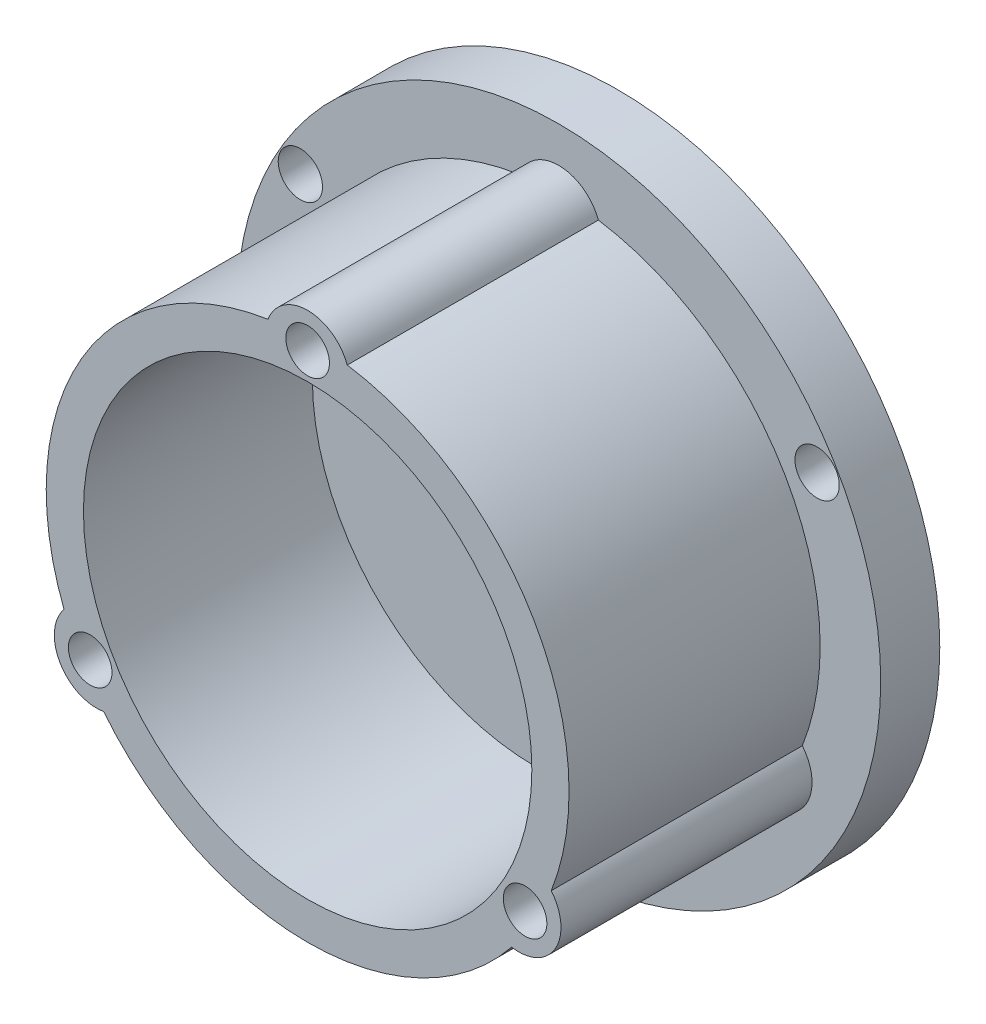
SolidWorks part; units mm, degrees
ref_plane "前视基准面" through (0, 0, 0) normal (0, 0, 1) x (1, 0, 0)
ref_plane "上视基准面" through (0, 0, 0) normal (0, 1, 0) x (1, 0, 0)
ref_plane "右视基准面" through (0, 0, 0) normal (1, 0, 0) x (0, 0, -1)
sketch "草图1" plane through (0, 0, 0) normal (0, 0, 1) x (1, 0, 0)
  circle A0 centre (0, 0) radius 15.75
  circle A1 centre (0, 0) radius 23 construction
  circle A3 centre (0, 0) radius 20
extrude "凸台-拉伸1" add sketch "草图1" along normal blind 5
sketch "草图2" plane through (0, 0, 5) normal (0, 0, 1) x (1, 0, 0)
  circle A0 centre (0, 0) radius 24 construction
  arc A2 (0, -25.8924) -> (22.4235, 12.9462) centre (20.7846, -12) ccw
  arc A3 (-22.4235, 12.9462) -> (0, -25.8924) centre (-20.7846, -12) ccw
  arc A5 (22.4235, 12.9462) -> (-22.4235, 12.9462) centre (0, 24) ccw
  point P12 (0, 0)
extrude "凸台-拉伸2" add sketch "草图2" along normal blind 8
sketch "草图3" plane through (0, 0, 13) normal (0, 0, 1) x (1, 0, 0)
  circle A0 centre (0, 42) radius 18
  circle A1 centre (36.3731, -21) radius 18
  circle A2 centre (-36.3731, -21) radius 18
  point P3 (0, 42)
  point P10 (0, 0)
  dimension "D1" = 3
  dimension "D3" = 42
extrude "凸台-拉伸3" add sketch "草图3" along normal blind 13
sketch "草图8" plane through (0, 0, 5) normal (0, 0, -1) x (-1, 0, 0)
  line L0 (0, 42) -> (36.3731, -21) construction
  line L1 (0, 0) -> (18.1865, 10.5) construction
  line L2 (18.1865, 10.5) -> (86.4245, 49.8972) construction
  line L3 (0, 0) -> (0, -8.0959) construction
  circle A0 centre (0, 0) radius 42 construction
  circle A4 centre (0, 42) radius 22
  circle A5 centre (36.3731, -21) radius 22
  circle A6 centre (-36.3731, -21) radius 22
  arc A7 (21.7226, 45.4827) -> (50.2505, -3.929) centre (100.7138, 58.1471) ccw
  arc A8 (-21.7226, 45.4827) -> (-50.2505, -3.929) centre (-100.7138, 58.1471) cw
  arc A9 (28.5279, -41.5537) -> (-28.5279, -41.5537) centre (0, -116.2943) ccw
  point P12 (0, 0)
  point P14 (0, 0)
  arc M7 (22.4235, 12.9462) -> (-22.4235, 12.9462) centre (0, 24) ccw
  arc M9 (-22.4235, 12.9462) -> (0, -25.8924) centre (-20.7846, -12) ccw
  arc M11 (0, -25.8924) -> (22.4235, 12.9462) centre (20.7846, -12) ccw
  dimension "D1" = 3
extrude "凸台-拉伸6" add sketch "草图8" against normal up to surface (8 mm away) contours A4 M7 | A7 A4 A5 M7 M11 | A5 M11 | A9 A5 A6 M11 M9 | A6 M9 | A4 A8 A6 M9 M7
sketch "草图4" plane through (0, 0, 26) normal (0, 0, 1) x (1, 0, 0)
  circle A0 centre (0, 42) radius 15
  circle A1 centre (36.3731, -21) radius 15
  circle A2 centre (-36.3731, -21) radius 15
  point P10 (0, 0)
  dimension "D1" = 3
extrude "切除-拉伸1" cut sketch "草图4" against normal blind 15.5
sketch "草图6" plane through (0, 0, 26) normal (0, 0, 1) x (1, 0, 0)
  arc A7 (2.6444, 56.7651) -> (-2.6444, 56.7651) centre (0, 58.5) ccw
  arc A11 (2.6444, 56.7651) -> (-2.6444, 56.7651) centre (0, 42) ccw
  arc A12 (11.4647, 32.3274) -> (14.1091, 36.9075) centre (14.2894, 33.75) ccw
  arc A13 (11.4647, 32.3274) -> (14.1091, 36.9075) centre (0, 42) ccw
  arc A14 (-14.1091, 36.9075) -> (-11.4647, 32.3274) centre (-14.2894, 33.75) ccw
  arc A15 (-14.1091, 36.9075) -> (-11.4647, 32.3274) centre (0, 42) ccw
  arc A16 (47.8378, -30.6726) -> (50.4822, -26.0925) centre (50.6625, -29.25) ccw
  arc A17 (47.8378, -30.6726) -> (50.4822, -26.0925) centre (36.3731, -21) ccw
  arc A18 (22.264, -26.0925) -> (24.9083, -30.6726) centre (22.0836, -29.25) ccw
  arc A19 (22.264, -26.0925) -> (24.9083, -30.6726) centre (36.3731, -21) ccw
  arc A20 (39.0174, -6.2349) -> (33.7287, -6.2349) centre (36.3731, -4.5) ccw
  arc A21 (39.0174, -6.2349) -> (33.7287, -6.2349) centre (36.3731, -21) ccw
  arc A22 (-50.4822, -26.0925) -> (-47.8378, -30.6726) centre (-50.6625, -29.25) ccw
  arc A23 (-50.4822, -26.0925) -> (-47.8378, -30.6726) centre (-36.3731, -21) ccw
  arc A24 (-33.7287, -6.2349) -> (-39.0174, -6.2349) centre (-36.3731, -4.5) ccw
  arc A25 (-33.7287, -6.2349) -> (-39.0174, -6.2349) centre (-36.3731, -21) ccw
  arc A26 (-24.9083, -30.6726) -> (-22.264, -26.0925) centre (-22.0836, -29.25) ccw
  arc A27 (-24.9083, -30.6726) -> (-22.264, -26.0925) centre (-36.3731, -21) ccw
  point P14 (0, 42)
  point P25 (36.3731, -21)
  point P37 (-36.3731, -21)
  point P38 (0, 0)
  dimension "D1" = 3
  dimension "D2" = 16.5
sketch "草图7" plane through (0, 0, 10.5) normal (0, 0, 1) x (1, 0, 0)
  circle A0 centre (0, 42) radius 3
  circle A1 centre (36.3731, -21) radius 3
  circle A2 centre (-36.3731, -21) radius 3
  point P3 (36.3731, -21)
  point P9 (0, 0)
  dimension "D1" = 3
extrude "切除-拉伸2" cut sketch "草图7" against normal blind 10
extrude "凸台-拉伸7" add sketch "草图6" against normal up to next
sketch "草图9" plane through (0, 0, 26) normal (0, 0, 1) x (1, 0, 0)
  circle A0 centre (0, 42) radius 17 construction
  circle A1 centre (0, 59) radius 1.475
  circle A2 centre (14.7224, 33.5) radius 1.475
  circle A3 centre (-14.7224, 33.5) radius 1.475
  circle A4 centre (51.0955, -29.5) radius 1.475
  circle A5 centre (21.6506, -29.5) radius 1.475
  circle A6 centre (36.3731, -4) radius 1.475
  circle A7 centre (36.3731, -21) radius 17 construction
  circle A8 centre (-51.0955, -29.5) radius 1.475
  circle A9 centre (-36.3731, -4) radius 1.475
  circle A10 centre (-21.6506, -29.5) radius 1.475
  circle A11 centre (-36.3731, -21) radius 17 construction
  point P12 (0, 42)
  point P21 (36.3731, -21)
  point P30 (-36.3731, -21)
  point P31 (0, 0)
  dimension "D1" = 3
  dimension "D2" = 3
extrude "切除-拉伸3" cut sketch "草图9" against normal blind 5
ref_plane "基准面1" through (0, 0, 2.5) normal (0, 0, -1) x (-1, 0, 0)
sketch "草图10" plane through (0, 0, 2.5) normal (0, 0, -1) x (-1, 0, 0)
  line L0 (0, 26.5971) -> (0, -28.7314) construction
  line L1 (0, 23.6711) -> (1.475, 23.6711)
  line L2 (1.475, 23.6711) -> (1.475, -24.2093)
  line L3 (1.475, -24.2093) -> (0, -24.2093)
  line L4 (0, -24.2093) -> (0, 23.6711)
revolve "切除-旋转1" cut sketch "草图10" angle 360 about L0
sketch "草图11" plane through (0, 0, 2.5) normal (0, 0, -1) x (-1, 0, 0)
  line L0 (-35.3446, 0) -> (29.9106, 0) construction
  line L1 (-23.6643, 0) -> (-23.6643, 1.475)
  line L2 (-23.6643, 1.475) -> (24.1188, 1.475)
  line L3 (24.1188, 1.475) -> (24.1188, 0)
  line L4 (24.1188, 0) -> (-23.6643, 0)
revolve "切除-旋转2" cut sketch "草图11" angle 360 about L0
sketch "草图12" plane through (0, 0, 5) normal (0, 0, -1) x (-1, 0, 0)
  line L0 (0, 42) -> (0, 32) construction
  line L1 (0, 32) -> (6.75, 32)
  line L2 (6.75, 32) -> (6.75, 60)
  line L4 (-6.75, 60) -> (-6.75, 32)
  line L5 (-6.75, 32) -> (0, 32)
  line L6 (6.75, 32) -> (6.75, 60)
  line L7 (6.75, 60) -> (-6.75, 60)
  line L8 (27.7128, -16) -> (24.3378, -21.8457)
  line L9 (24.3378, -21.8457) -> (48.5865, -35.8457)
  line L10 (55.3365, -24.1543) -> (31.0878, -10.1543)
  line L11 (31.0878, -10.1543) -> (27.7128, -16)
  line L12 (24.3378, -21.8457) -> (48.5865, -35.8457)
  line L13 (48.5865, -35.8457) -> (55.3365, -24.1543)
  line L14 (36.3731, -21) -> (27.7128, -16) construction
  line L15 (-27.7128, -16) -> (-31.0878, -10.1543)
  line L16 (-31.0878, -10.1543) -> (-55.3365, -24.1543)
  line L17 (-48.5865, -35.8457) -> (-24.3378, -21.8457)
  line L18 (-24.3378, -21.8457) -> (-27.7128, -16)
  line L19 (-31.0878, -10.1543) -> (-55.3365, -24.1543)
  line L20 (-55.3365, -24.1543) -> (-48.5865, -35.8457)
  line L21 (-36.3731, -21) -> (-27.7128, -16) construction
  point P5 (0, 60)
  point P22 (0, 0)
  dimension "D1" = 10
  dimension "D2" = 28
  dimension "D3" = 13.5
  dimension "D4" = 3
extrude "切除-拉伸4" cut sketch "草图12" against normal blind 2
sketch "草图13" plane through (0, 0, 26) normal (0, 0, 1) x (1, 0, 0)
  circle A0 centre (0, 42) radius 15.15
  circle A1 centre (36.3731, -21) radius 15.25
  circle A2 centre (-36.3731, -21) radius 15.18
extrude "切除-拉伸5" cut sketch "草图13" against normal up to surface (15.5 mm away) up to face at (-33.3731, -21, 10.5)
sketch "草图14" plane through (0, 0, 5) normal (0, 0, -1) x (-1, 0, 0)
  circle A0 centre (0, 0) radius 15.75
extrude "切除-拉伸6" cut sketch "草图14" against normal up to surface (8 mm away) up to face at (-36.3731, -21, 13)
sketch "草图15" plane through (0, 0, 26) normal (0, 0, 1) x (1, 0, 0)
  circle A6 centre (-36.3731, -21) radius 110.7353
  arc A7 (-39.0572, -3.5047) -> (-52.8665, -27.4232) centre (-36.3731, -21) ccw
  arc A8 (-52.8665, -27.4232) -> (-50.1824, -32.0721) centre (-50.6625, -29.25) ccw
  arc A9 (-50.1824, -32.0721) -> (-22.5637, -32.0721) centre (-36.3731, -21) ccw
  arc A10 (-22.5637, -32.0721) -> (-19.8796, -27.4232) centre (-22.0836, -29.25) ccw
  arc A11 (-19.8796, -27.4232) -> (-33.689, -3.5047) centre (-36.3731, -21) ccw
  arc A12 (-33.689, -3.5047) -> (-39.0572, -3.5047) centre (-36.3731, -4.5) ccw
  point P14 (-36.3731, -21)
ref_plane "基准面2" through (0, 0, 9) normal (0, 0, -1) x (-1, 0, 0)
extrude "切除-拉伸8" cut sketch "草图15" against normal up to surface (17 mm away)
sketch "草图16" plane through (0, 0, 9) normal (0, 0, -1) x (-1, 0, 0)
  circle A1 centre (36.3731, -21) radius 128.1735
  circle A2 centre (36.3731, -21) radius 21.8
extrude "切除-拉伸10" cut sketch "草图16" along normal up to surface (9 mm away) up to face at (20, 0, 0)
sketch "草图18" plane through (0, 0, 7) normal (0, 0, -1) x (-1, 0, 0)
  circle A0 centre (36.3731, -21) radius 4.1
extrude "切除-拉伸12" cut sketch "草图18" against normal blind 10
sketch "草图19" plane through (0, 0, 5) normal (0, 0, -1) x (-1, 0, 0)
  circle A0 centre (36.3731, -21) radius 20.2 construction
  circle A1 centre (36.3731, -41.2) radius 1.5
  circle A2 centre (18.8794, -10.9) radius 1.5
  circle A3 centre (53.8668, -10.9) radius 1.5
  point P11 (36.3731, -21)
extrude "切除-拉伸14" cut sketch "草图19" against normal blind 10
